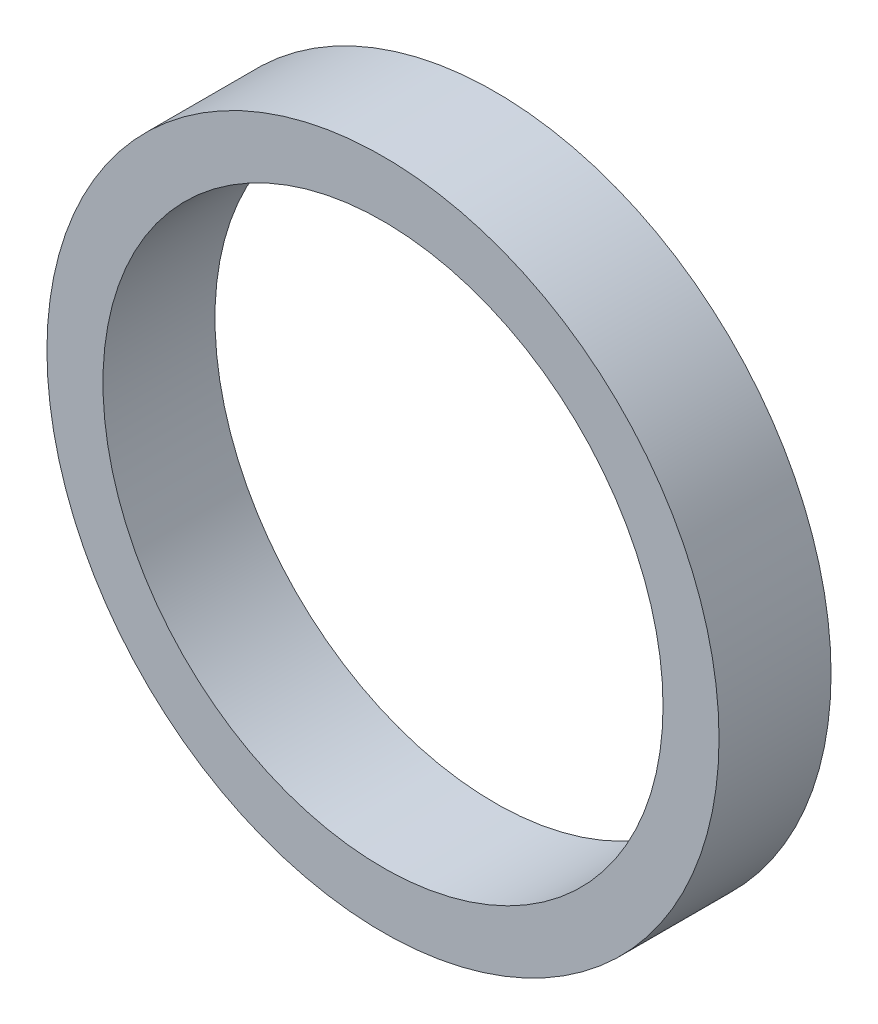
SolidWorks part; units mm, degrees
ref_plane "Спереди" through (0, 0, 0) normal (0, 0, 1) x (1, 0, 0)
ref_plane "Сверху" through (0, 0, 0) normal (0, 1, 0) x (1, 0, 0)
ref_plane "Справа" through (0, 0, 0) normal (1, 0, 0) x (0, 0, -1)
sketch "Эскиз1" plane through (0, 0, 0) normal (0, 0, 1) x (1, 0, 0)
  circle A0 centre (0, 0) radius 20
  circle A1 centre (0, 0) radius 24
  dimension "D1" = 40
  dimension "D2" = 48
extrude "Бобышка-Вытянуть1" add sketch "Эскиз1" along normal blind 8
